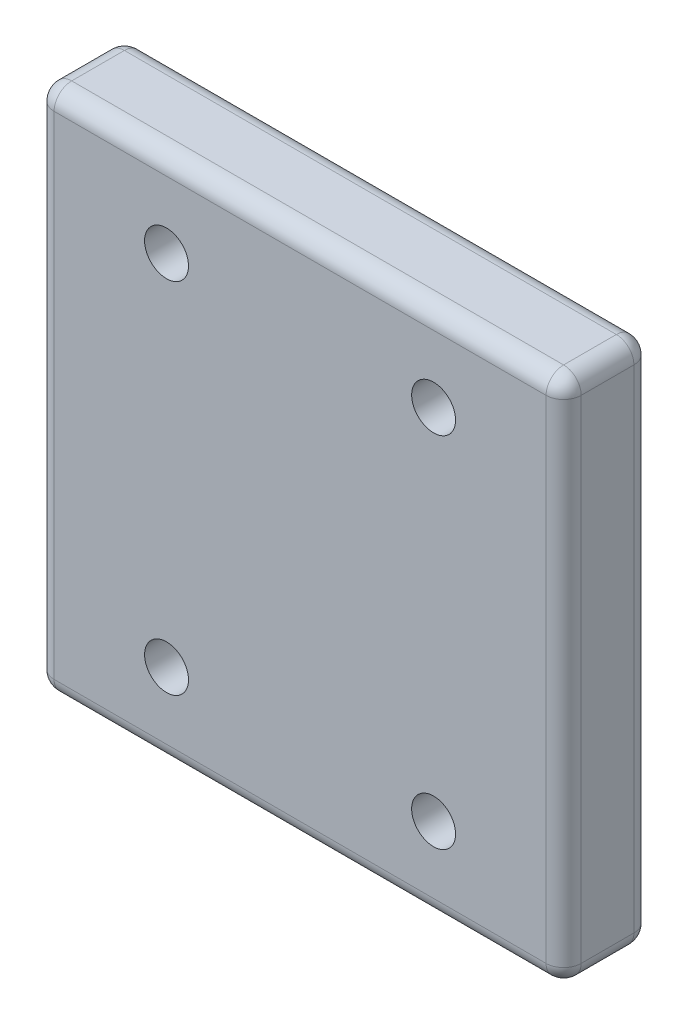
SolidWorks part; units mm, degrees
material "AISI 316 Stainless Steel Sheet (SS)"
ref_plane "Front Plane" through (0, 0, 0) normal (0, 0, 1) x (1, 0, 0)
ref_plane "Top Plane" through (0, 0, 0) normal (0, 1, 0) x (1, 0, 0)
ref_plane "Right Plane" through (0, 0, 0) normal (1, 0, 0) x (0, 0, -1)
sketch "Sketch1" plane through (0, 0, 0) normal (0, 0, 1) x (1, 0, 0)
  line L0 (-9.525, 9.525) -> (-9.525, -9.525)
  line L1 (-9.525, -9.525) -> (9.525, -9.525)
  line L2 (9.525, -9.525) -> (9.525, 9.525)
  line L3 (9.525, 9.525) -> (-9.525, 9.525)
  line L4 (-9.525, 9.525) -> (9.525, -9.525) construction
  line L5 (9.525, 9.525) -> (-9.525, -9.525) construction
  line L6 (-4.826, 9.525) -> (-4.826, -9.525) construction
  line L7 (4.826, 9.525) -> (4.826, -9.525) construction
  line L8 (-9.525, -6.477) -> (9.525, -6.477) construction
  line L9 (-9.525, 0) -> (9.525, 0) construction
  circle A0 centre (-4.826, -6.477) radius 0.7938
  circle A1 centre (4.826, -6.477) radius 0.7938
  circle A2 centre (4.826, 6.477) radius 0.7938
  circle A3 centre (-4.826, 6.477) radius 0.7938
  point P2 (0, 0)
  dimension "D6" = 1.5875
  dimension "D7" = 1.5875
  dimension "D1" = 19.05
  dimension "D2" = 19.05
  dimension "D3" = 4.826
  dimension "D4" = 4.826
  dimension "D5" = 3.048
extrude "Boss-Extrude1" add sketch "Sketch1" along normal blind 3.175
fillet "Fillet2" radius 0.635 12 edges at (0, -9.525, 3.175) (0, -9.525, 0) (-9.525, 0, 3.175) (-9.525, -9.525, 1.5875) (-9.525, 0, 0) (0, 9.525, 3.175) (-9.525, 9.525, 1.5875) (0, 9.525, 0) (9.525, -9.525, 1.5875) (9.525, 0, 3.175) (9.525, 9.525, 1.5875) (9.525, 0, 0)
